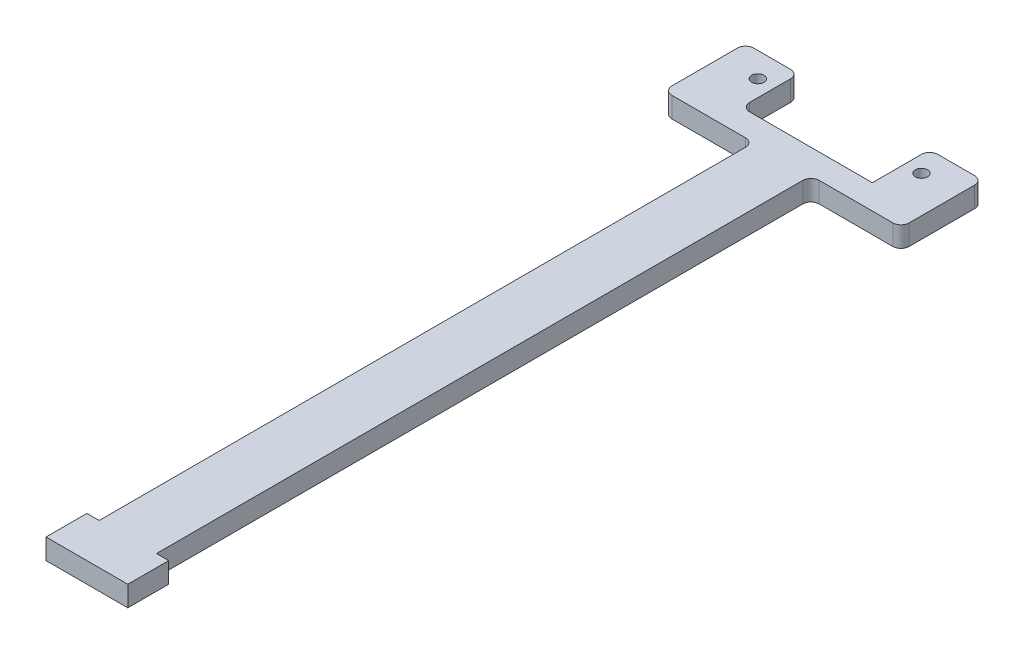
SolidWorks part; units mm, degrees
ref_plane "Front Plane" through (0, 0, 0) normal (0, 0, 1) x (1, 0, 0)
ref_plane "Top Plane" through (0, 0, 0) normal (0, 1, 0) x (1, 0, 0)
ref_plane "Right Plane" through (0, 0, 0) normal (1, 0, 0) x (0, 0, -1)
sketch "Sketch1" plane through (0, 0, 0) normal (0, 1, 0) x (1, 0, 0)
  line L1 (9, -10) -> (9, 0)
  line L2 (9, 0) -> (6, 0)
  line L3 (6, 0) -> (6, 160)
  line L4 (6, 160) -> (28, 160)
  line L5 (28, 160) -> (28, 180)
  line L6 (28, 180) -> (-30, 180)
  line L7 (-30, 180) -> (-30, 160)
  line L8 (-30, 160) -> (-8, 160)
  line L9 (-8, 160) -> (-8, 0)
  line L10 (-8, 0) -> (-11, 0)
  line L11 (-11, 0) -> (-11, -10)
  line L13 (-11, -10) -> (9, -10)
  dimension "D1" = 20
  dimension "D2" = 160
  dimension "D3" = 10
  dimension "D4" = 14
  dimension "D5" = 3
  dimension "D6" = 58
  dimension "D7" = 22
  dimension "D8" = 20
  dimension "D9" = 10
  dimension "D10" = 6
extrude "Boss-Extrude1" add sketch "Sketch1" along normal blind 5
sketch "Sketch2" plane through (0, 5, 0) normal (0, 1, 0) x (1, 0, 0)
  line L0 (-30, 180) -> (-30, 160) construction
  line L1 (28, 180) -> (-30, 180) construction
  line L2 (-17, 180) -> (-17, 166)
  line L3 (-17, 166) -> (15, 166)
  line L4 (15, 166) -> (15, 180)
  line L5 (-17, 180) -> (15, 180)
  circle A0 centre (-21, 174) radius 1.5
  circle A1 centre (19, 174) radius 1.5
  dimension "D1" = 3
  dimension "D2" = 3
  dimension "D3" = 40
  dimension "D4" = 9
  dimension "D5" = 6
  dimension "D6" = 6
  dimension "D7" = 32
  dimension "D8" = 14
  dimension "D9" = 13
extrude "Cut-Extrude1" cut sketch "Sketch2" against normal blind 10
fillet "Fillet1" radius 2 9 edges at (6, 2.5, -160) (-8, 2.5, -160) (-30, 2.5, -160) (28, 2.5, -160) (28, 2.5, -180) (15, 2.5, -180) (-17, 2.5, -166) (-17, 2.5, -180) (-30, 2.5, -180)
